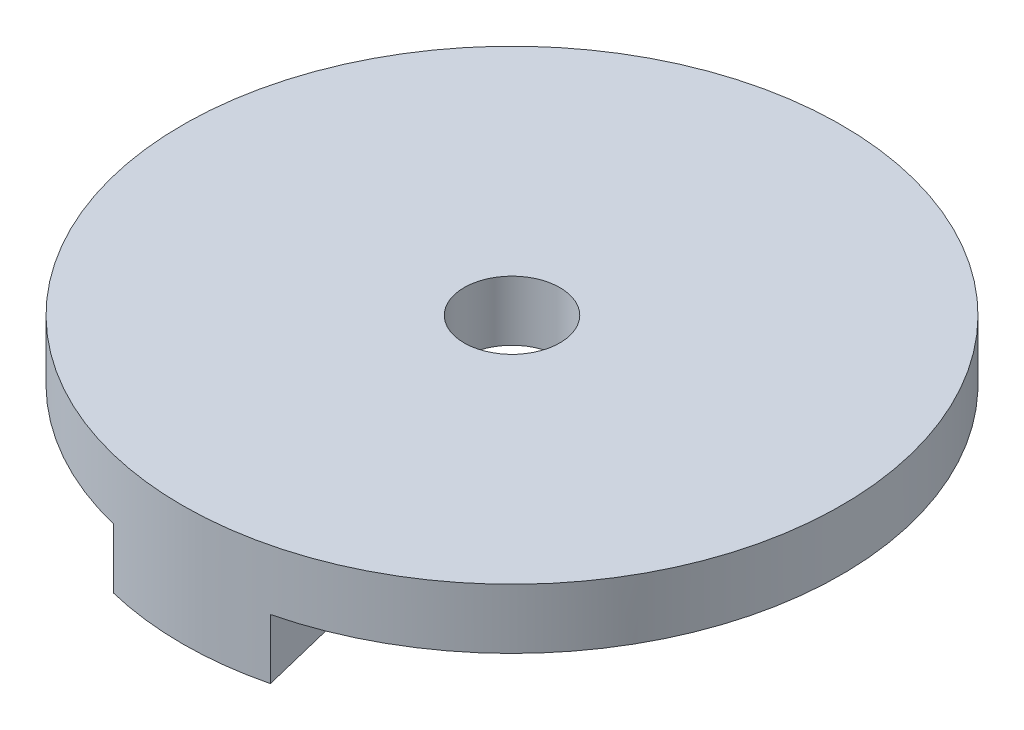
SolidWorks part; units mm, degrees
material "AISI 304"
ref_plane "Plan de face" through (0, 0, 0) normal (0, 0, 1) x (1, 0, 0)
ref_plane "Plan de dessus" through (0, 0, 0) normal (0, 1, 0) x (1, 0, 0)
ref_plane "Plan de droite" through (0, 0, 0) normal (1, 0, 0) x (0, 0, -1)
sketch "Sketch2" plane through (0, 0, 0) normal (0, 1, 0) x (1, 0, 0)
  circle A0 centre (0, 0) radius 34.925
  circle A1 centre (0, 0) radius 5.08
  dimension "D1" = 69.85
  dimension "D2" = 10.16
extrude "Boss-Extrude1" add sketch "Sketch2" along normal blind 6.35
sketch "Sketch3" plane through (0, 0, 0) normal (0, -1, 0) x (1, 0, 0)
  line L0 (6.35, 25.903) -> (8.3155, 33.9206)
  line L1 (0, -6.985) -> (0, 6.985) construction
  line L2 (-6.35, 25.903) -> (-8.3155, 33.9206)
  arc A0 (8.3155, 33.9206) -> (-8.3155, 33.9206) centre (0, 0) ccw
  arc A1 (6.35, 25.903) -> (-6.35, 25.903) centre (0, 0) ccw
  circle A2 centre (0, 0) radius 34.925 construction
  point P1 (-6.6746, 27.2272)
  dimension "D1" = 53.34
  dimension "D2" = 12.7
extrude "Boss-Extrude2" add sketch "Sketch3" along normal blind 6.35
